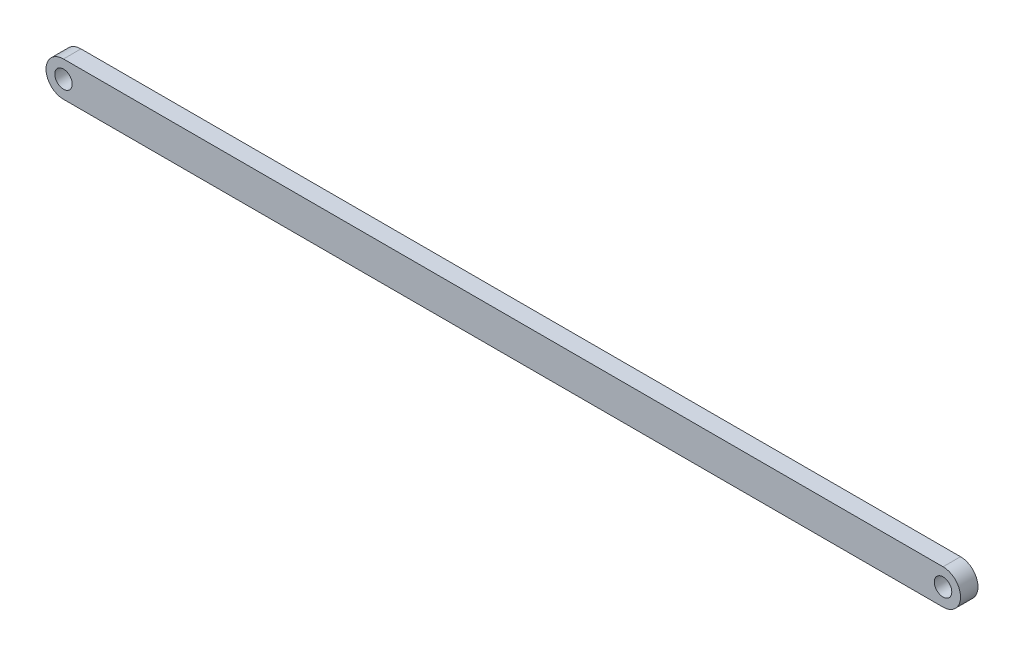
SolidWorks part; units mm, degrees
ref_plane "Plano frontal" through (0, 0, 0) normal (0, 0, 1) x (1, 0, 0)
ref_plane "Plano superior" through (0, 0, 0) normal (0, 1, 0) x (1, 0, 0)
ref_plane "Plano direito" through (0, 0, 0) normal (1, 0, 0) x (0, 0, -1)
sketch "Esboço1" plane through (0, 0, 0) normal (0, 0, 1) x (1, 0, 0)
  line L0 (-125.84, 5) -> (125.84, 5)
  line L1 (-125.84, 0) -> (125.84, 0) construction
  line L2 (-125.84, -5) -> (125.84, -5)
  arc A0 (-125.84, 5) -> (-125.84, -5) centre (-125.84, 0) ccw
  arc A1 (125.84, 5) -> (125.84, -5) centre (125.84, 0) cw
  circle A2 centre (-125.84, 0) radius 2.5
  circle A3 centre (125.84, 0) radius 2.5
  point P3 (0, 5)
  dimension "D1" = 251.68
  dimension "D2" = 5
extrude "Ressalto-extrusão1" add sketch "Esboço1" along normal blind 5
